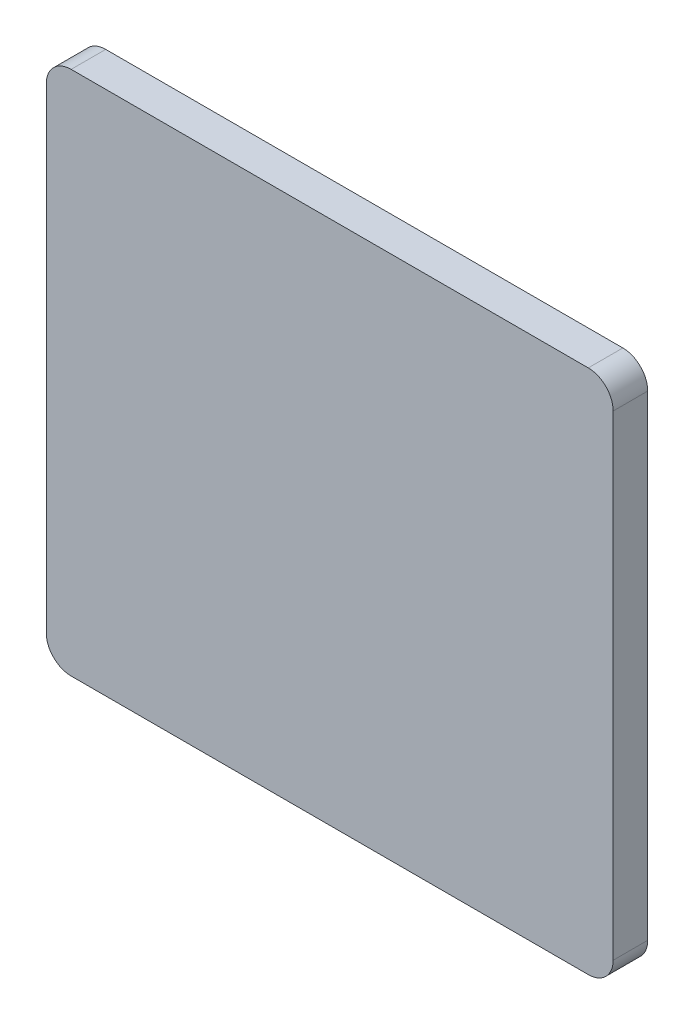
SolidWorks part; units mm, degrees
ref_plane "前视基准面" through (0, 0, 0) normal (0, 0, 1) x (1, 0, 0)
ref_plane "上视基准面" through (0, 0, 0) normal (0, 1, 0) x (1, 0, 0)
ref_plane "右视基准面" through (0, 0, 0) normal (1, 0, 0) x (0, 0, -1)
other "Configuration Table"
sketch "Factory_snap_lid_Sketch" plane through (0, 0, 0) normal (0, 0, 1) x (1, 0, 0)
  line L0 (-18.7, -19) -> (18.7, -19)
  line L1 (20.5, -17.2) -> (20.5, 17.2)
  line L2 (18.7, 19) -> (-18.7, 19)
  line L3 (-20.5, 17.2) -> (-20.5, -17.2)
  arc A0 (18.7, -19) -> (20.5, -17.2) centre (18.7, -17.2) ccw
  arc A1 (20.5, 17.2) -> (18.7, 19) centre (18.7, 17.2) ccw
  arc A2 (-18.7, 19) -> (-20.5, 17.2) centre (-18.7, 17.2) ccw
  arc A3 (-20.5, -17.2) -> (-18.7, -19) centre (-18.7, -17.2) ccw
extrude "Factory_snap_lid" add sketch "Factory_snap_lid_Sketch" along normal blind 2.5 separate body
sketch "Moulded_lid_underside_relief_Sketch" plane through (0, 0, 0) normal (0, 0, 1) x (1, 0, 0)
  line L0 (-17.4, -16.9) -> (17.4, -16.9)
  line L1 (18.4, -15.9) -> (18.4, 15.9)
  line L2 (17.4, 16.9) -> (-17.4, 16.9)
  line L3 (-18.4, 15.9) -> (-18.4, -15.9)
  arc A0 (17.4, -16.9) -> (18.4, -15.9) centre (17.4, -15.9) ccw
  arc A1 (18.4, 15.9) -> (17.4, 16.9) centre (17.4, 15.9) ccw
  arc A2 (-17.4, 16.9) -> (-18.4, 15.9) centre (-17.4, 15.9) ccw
  arc A3 (-18.4, -15.9) -> (-17.4, -16.9) centre (-17.4, -15.9) ccw
extrude "Moulded_lid_underside_relief" cut sketch "Moulded_lid_underside_relief_Sketch" along normal blind 0.7
